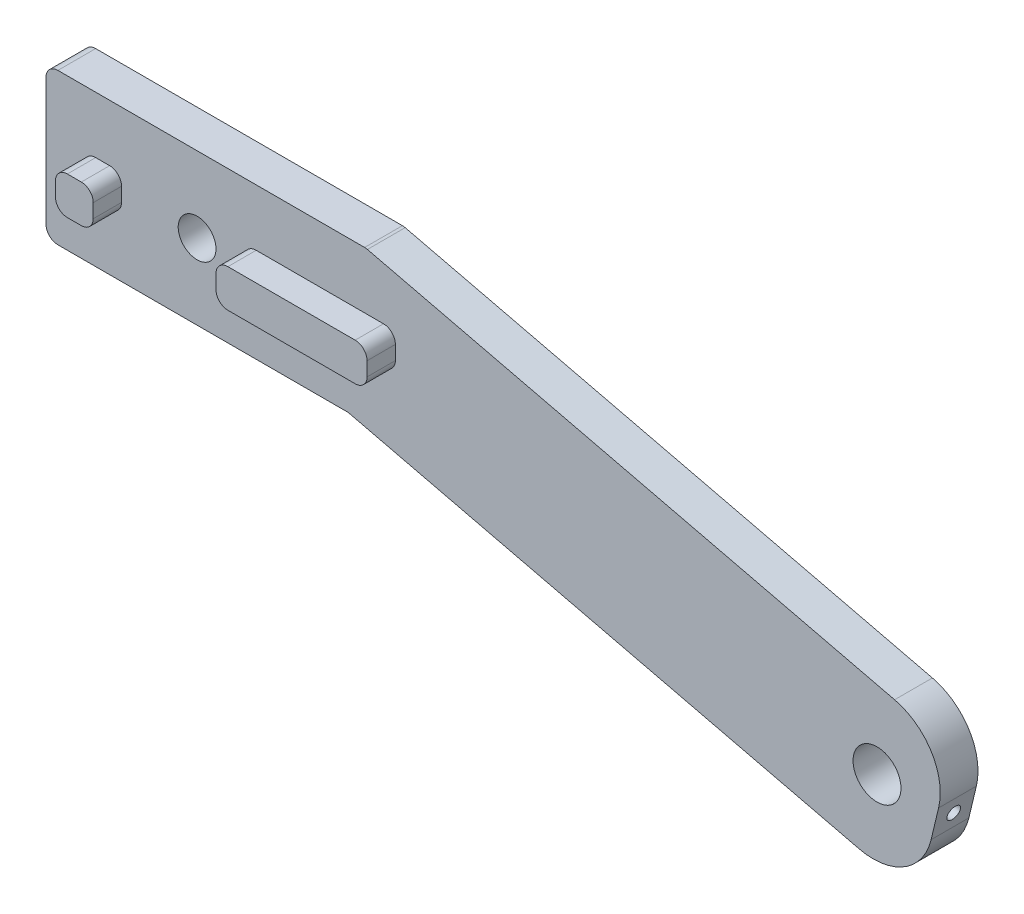
SolidWorks part; units mm, degrees
ref_plane "Front Plane" through (0, 0, 0) normal (0, 0, 1) x (1, 0, 0)
ref_plane "Top Plane" through (0, 0, 0) normal (0, 1, 0) x (1, 0, 0)
ref_plane "Right Plane" through (0, 0, 0) normal (1, 0, 0) x (0, 0, -1)
sketch "Sketch1" plane through (0, 0, 0) normal (0, 0, 1) x (1, 0, 0)
  line L0 (-12.7, 0) -> (-38.1, 0) construction
  line L2 (-38.1, -12.7) -> (-38.1, 12.7)
  line L5 (104.5604, -8.5999) -> (98.6396, -33.3001) construction
  line L6 (12.7, -12.7) -> (71.3084, -26.7487) construction
  line L19 (-12.7, 0) -> (0, 0) construction
  line L25 (15.7017, 12.7) -> (-38.1, 12.7)
  line L26 (12.7, -12.7) -> (-38.1, -12.7)
  line L27 (15.7017, 12.7) -> (74.6646, -1.4337) construction
  line L28 (15.7017, 12.7) -> (114.2849, -10.9309)
  line L29 (12.7, -12.7) -> (108.3641, -35.6312)
  line L30 (108.3641, -35.6312) -> (114.2849, -10.9309)
  circle A0 centre (-12.7, 0) radius 3.175
  circle A13 centre (101.6, -20.95) radius 4.025
  dimension "D4" = 6.35
  dimension "D7" = 10
  dimension "D8" = 25.4
  dimension "D5" = 101.6
  dimension "D6" = 20.95
  dimension "D9" = 8.05
  dimension "D2" = 12.7
  dimension "D3" = 25.4
  dimension "D12" = 12.7
  dimension "D13" = 25.4
extrude "Boss-Extrude1" add sketch "Sketch1" along normal blind 6.35
sketch "Sketch3" plane through (110.5529, -26.5001, 0) normal (0.9725, -0.2331, 0) x (0, 0, -1)
  line L0 (-6.35, 3.3102) -> (0, 3.3102) construction
  line L1 (-6.35, -9.3898) -> (-6.35, 16.0102) construction
  line L2 (0, -9.3898) -> (0, 16.0102) construction
  circle A0 centre (-3.175, 3.3102) radius 1.1303
  dimension "D1" = 2.2606
extrude "Cut-Extrude2" cut sketch "Sketch3" against normal up to next
fillet "Fillet4" radius 10 2 edges at (108.3641, -35.6312, 3.175) (114.2849, -10.9309, 3.175)
sketch "Sketch4" plane through (0, 0, 6.35) normal (0, 0, 1) x (1, 0, 0)
  line L0 (-25.4, -3.175) -> (-25.4, 3.175)
  line L1 (-25.4, -3.175) -> (-31.75, -3.175)
  line L2 (-25.4, 3.175) -> (-31.75, 3.175)
  line L3 (-31.75, -3.175) -> (-31.75, 3.175)
  line L4 (-25.4, -3.175) -> (-31.75, 3.175) construction
  line L5 (-25.4, 3.175) -> (-31.75, -3.175) construction
  line L6 (-38.1, 0) -> (0, 0) construction
  line L7 (0, 0) -> (68.6835, 0) construction
  line L8 (-4.7625, -3.175) -> (-4.7625, 3.175)
  line L9 (-4.7625, -3.175) -> (20.6375, -3.175)
  line L10 (-4.7625, 3.175) -> (20.6375, 3.175)
  line L11 (20.6375, -3.175) -> (20.6375, 3.175)
  line L12 (-4.7625, -3.175) -> (20.6375, 3.175) construction
  line L13 (-4.7625, 3.175) -> (20.6375, -3.175) construction
  line L14 (-38.1, 12.7) -> (-38.1, -12.7) construction
  line L15 (104.5604, -8.5999) -> (15.7017, 12.7) construction
  point P1 (-28.575, 0)
  point P3 (0, 0)
  point P8 (68.6835, 0)
  point P14 (7.9375, 0)
  point P15 (-12.7, 0)
  dimension "D2" = 6.35
  dimension "D1" = 6.35
  dimension "D3" = 7.9375
  dimension "D4" = 25.4
  dimension "D5" = 12.7
extrude "Boss-Extrude2" add sketch "Sketch4" along normal blind 4.7625
fillet "Fillet3" radius 2 12 edges at (-38.1, -12.7, 3.175) (-38.1, 12.7, 3.175) (12.7, -12.7, 3.175) (15.7017, 12.7, 3.175) (20.6375, -3.175, 8.7312) (20.6375, 3.175, 8.7312) (-4.7625, 3.175, 8.7312) (-4.7625, -3.175, 8.7312) (-31.75, 3.175, 8.7312) (-31.75, -3.175, 8.7312) (-25.4, -3.175, 8.7312) (-25.4, 3.175, 8.7312)
